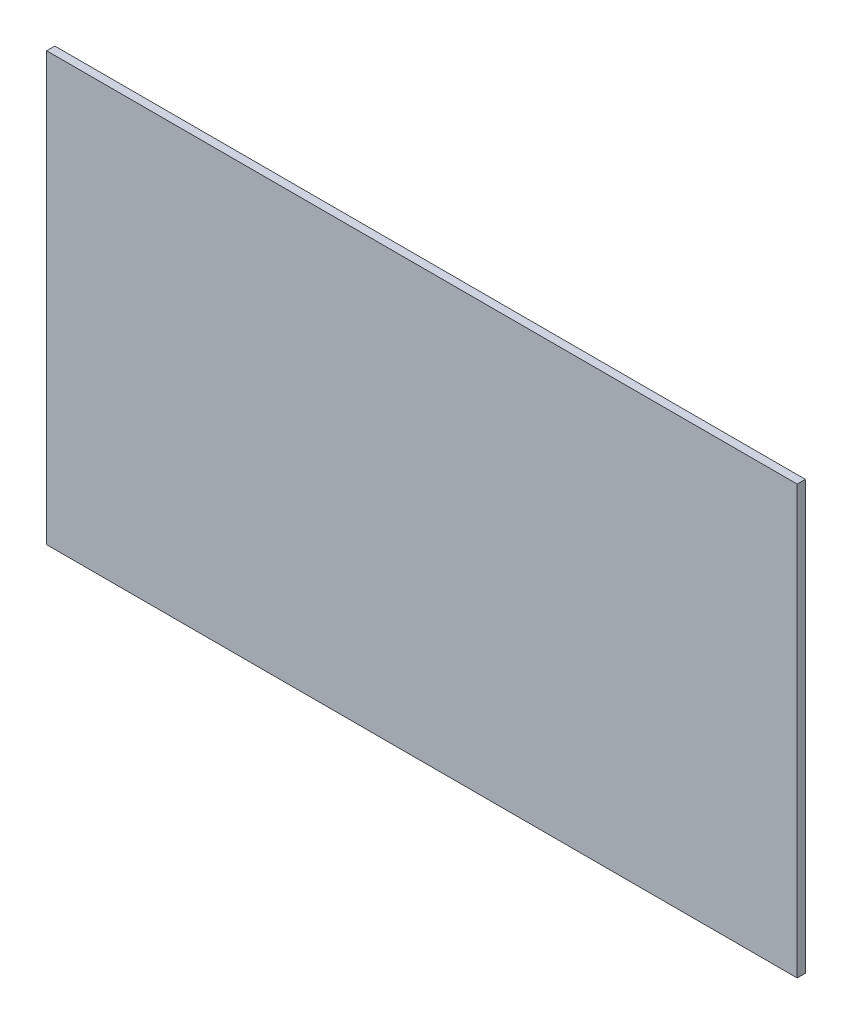
SolidWorks part; units mm, degrees
ref_plane "Front Plane" through (0, 0, 0) normal (0, 0, 1) x (1, 0, 0)
ref_plane "Top Plane" through (0, 0, 0) normal (0, 1, 0) x (1, 0, 0)
ref_plane "Right Plane" through (0, 0, 0) normal (1, 0, 0) x (0, 0, -1)
sketch "Sketch1" plane through (0, 0, 0) normal (0, 0, 1) x (1, 0, 0)
  line L1 (0, 0) -> (93, 0)
  line L2 (0, 0) -> (0, 53)
  line L3 (0, 53) -> (93, 53)
  line L4 (93, 0) -> (93, 53)
  dimension "D1" = 93
  dimension "D2" = 53
extrude "Boss-Extrude1" add sketch "Sketch1" along normal blind 1.016
